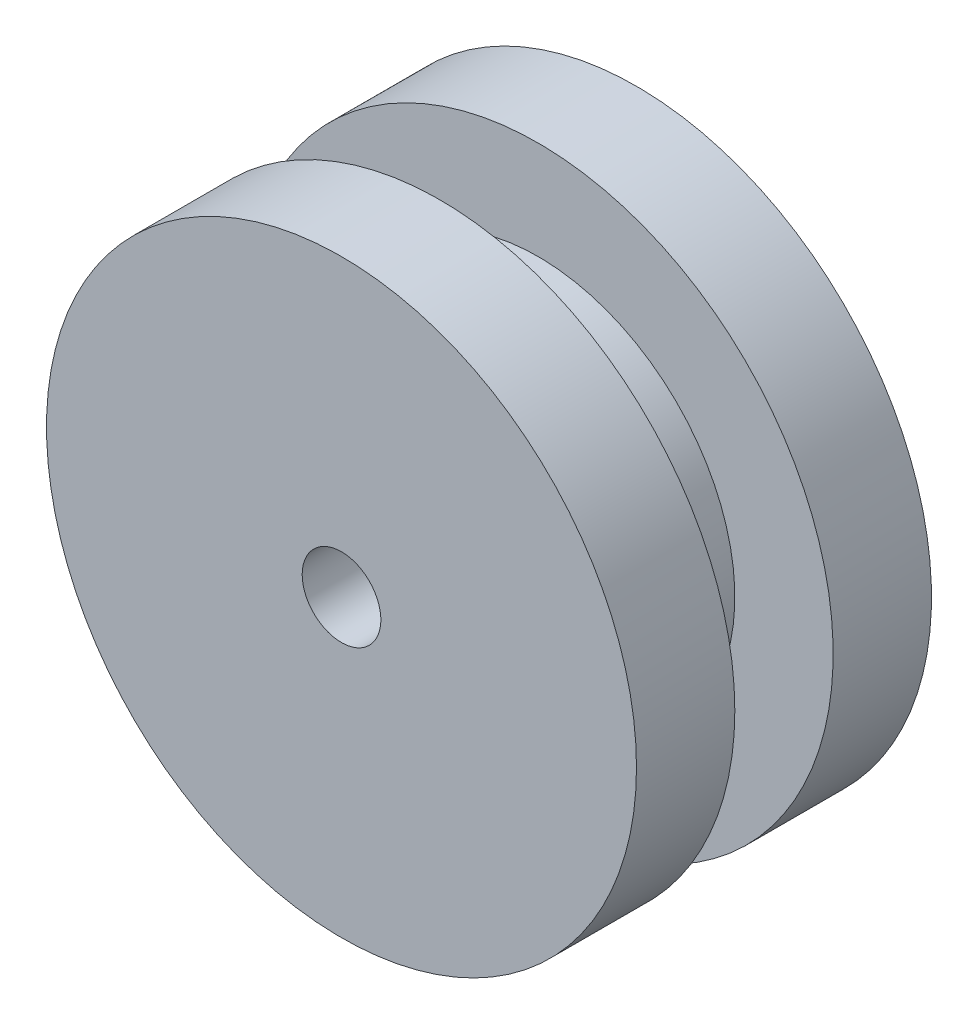
SolidWorks part; units mm, degrees
ref_plane "Front Plane" through (0, 0, 0) normal (0, 0, 1) x (1, 0, 0)
ref_plane "Top Plane" through (0, 0, 0) normal (0, 1, 0) x (1, 0, 0)
ref_plane "Right Plane" through (0, 0, 0) normal (1, 0, 0) x (0, 0, -1)
sketch "Sketch1" plane through (0, 0, 0) normal (0, 0, 1) x (1, 0, 0)
  circle A0 centre (0, 0) radius 20
extrude "Extrude1" add sketch "Sketch1" along normal mid plane 10
sketch "Sketch2" plane through (0, 0, 5) normal (0, 0, 1) x (1, 0, 0)
  circle A0 centre (0, 0) radius 30
  dimension "D1" = 60
extrude "Extrude2" add sketch "Sketch2" along normal blind 10
sketch "Sketch3" plane through (0, 0, -5) normal (0, 0, -1) x (-1, 0, 0)
  circle A0 centre (0, 0) radius 30
extrude "Extrude3" add sketch "Sketch3" along normal blind 10
sketch "Sketch4" plane through (0, 0, -15) normal (0, 0, -1) x (-1, 0, 0)
  circle A0 centre (0, 0) radius 4
extrude "Cut-Extrude1" cut sketch "Sketch4" against normal blind 30
